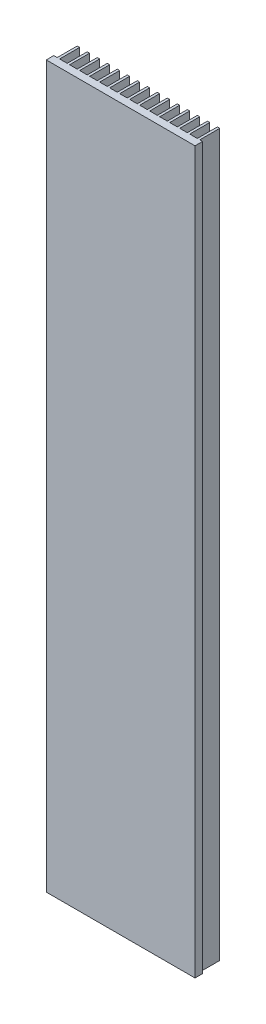
SolidWorks part; units mm, degrees
material "6063-T5"
ref_plane "X-Y Datum" through (0, 0, 0) normal (0, 0, 1) x (1, 0, 0)
ref_plane "X-Z Datum" through (0, 0, 0) normal (0, 1, 0) x (1, 0, 0)
ref_plane "Y-Z Datum" through (0, 0, 0) normal (1, 0, 0) x (0, 0, -1)
sketch "Sketch1" plane through (0, 0, 0) normal (0, 1, 0) x (1, 0, 0)
  line L0 (0, 9.525) -> (4.0132, 9.525) construction
  line L1 (0, 0) -> (136.525, 0)
  line L2 (0, 0) -> (0, 9.525)
  line L3 (0, 9.525) -> (4.0132, 9.525)
  line L4 (136.525, 0) -> (136.525, 9.525)
  line L5 (4.7752, 9.525) -> (4.7752, 34.925) construction
  line L6 (4.0132, 34.925) -> (4.0132, 9.525)
  line L7 (5.5372, 34.925) -> (5.5372, 9.525)
  line L8 (11.8872, 34.925) -> (11.8872, 9.525)
  line L9 (10.3632, 34.925) -> (10.3632, 9.525)
  line L10 (18.2372, 34.925) -> (18.2372, 9.525)
  line L11 (16.7132, 34.925) -> (16.7132, 9.525)
  line L12 (24.5872, 34.925) -> (24.5872, 9.525)
  line L13 (23.0632, 34.925) -> (23.0632, 9.525)
  line L14 (30.9372, 34.925) -> (30.9372, 9.525)
  line L15 (29.4132, 34.925) -> (29.4132, 9.525)
  line L16 (37.2872, 34.925) -> (37.2872, 9.525)
  line L17 (35.7632, 34.925) -> (35.7632, 9.525)
  line L18 (43.6372, 34.925) -> (43.6372, 9.525)
  line L19 (42.1132, 34.925) -> (42.1132, 9.525)
  line L20 (49.9872, 34.925) -> (49.9872, 9.525)
  line L21 (48.4632, 34.925) -> (48.4632, 9.525)
  line L22 (56.3372, 34.925) -> (56.3372, 9.525)
  line L23 (54.8132, 34.925) -> (54.8132, 9.525)
  line L24 (62.6872, 34.925) -> (62.6872, 9.525)
  line L25 (61.1632, 34.925) -> (61.1632, 9.525)
  line L26 (69.0372, 34.925) -> (69.0372, 9.525)
  line L27 (67.5132, 34.925) -> (67.5132, 9.525)
  line L28 (75.3872, 34.925) -> (75.3872, 9.525)
  line L29 (73.8632, 34.925) -> (73.8632, 9.525)
  line L30 (81.7372, 34.925) -> (81.7372, 9.525)
  line L31 (80.2132, 34.925) -> (80.2132, 9.525)
  line L32 (88.0872, 34.925) -> (88.0872, 9.525)
  line L33 (86.5632, 34.925) -> (86.5632, 9.525)
  line L34 (94.4372, 34.925) -> (94.4372, 9.525)
  line L35 (92.9132, 34.925) -> (92.9132, 9.525)
  line L36 (100.7872, 34.925) -> (100.7872, 9.525)
  line L37 (99.2632, 34.925) -> (99.2632, 9.525)
  line L38 (107.1372, 34.925) -> (107.1372, 9.525)
  line L39 (105.6132, 34.925) -> (105.6132, 9.525)
  line L40 (113.4872, 34.925) -> (113.4872, 9.525)
  line L41 (111.9632, 34.925) -> (111.9632, 9.525)
  line L42 (119.8372, 34.925) -> (119.8372, 9.525)
  line L43 (118.3132, 34.925) -> (118.3132, 9.525)
  line L44 (126.1872, 34.925) -> (126.1872, 9.525)
  line L45 (124.6632, 34.925) -> (124.6632, 9.525)
  line L46 (132.5372, 34.925) -> (132.5372, 9.525)
  line L47 (131.0132, 34.925) -> (131.0132, 9.525)
  line L48 (5.5372, 9.525) -> (10.3632, 9.525)
  line L49 (11.8872, 9.525) -> (16.7132, 9.525)
  line L50 (24.5872, 9.525) -> (29.4132, 9.525)
  line L51 (30.9372, 9.525) -> (35.7632, 9.525)
  line L52 (18.2372, 9.525) -> (23.0632, 9.525)
  line L53 (37.2872, 9.525) -> (42.1132, 9.525)
  line L54 (43.6372, 9.525) -> (48.4632, 9.525)
  line L55 (49.9872, 9.525) -> (54.8132, 9.525)
  line L56 (56.3372, 9.525) -> (61.1632, 9.525)
  line L57 (62.6872, 9.525) -> (67.5132, 9.525)
  line L58 (69.0372, 9.525) -> (73.8632, 9.525)
  line L59 (75.3872, 9.525) -> (80.2132, 9.525)
  line L60 (81.7372, 9.525) -> (86.5632, 9.525)
  line L61 (88.0872, 9.525) -> (92.9132, 9.525)
  line L62 (94.4372, 9.525) -> (99.2632, 9.525)
  line L63 (100.7872, 9.525) -> (105.6132, 9.525)
  line L64 (107.1372, 9.525) -> (111.9632, 9.525)
  line L65 (113.4872, 9.525) -> (118.3132, 9.525)
  line L66 (119.8372, 9.525) -> (124.6632, 9.525)
  line L67 (126.1872, 9.525) -> (131.0132, 9.525)
  line L68 (132.5372, 9.525) -> (136.525, 9.525)
  arc A0 (5.5372, 34.925) -> (4.0132, 34.925) centre (4.7752, 34.925) ccw
  arc A1 (11.8872, 34.925) -> (10.3632, 34.925) centre (11.1252, 34.925) ccw
  arc A2 (18.2372, 34.925) -> (16.7132, 34.925) centre (17.4752, 34.925) ccw
  arc A3 (24.5872, 34.925) -> (23.0632, 34.925) centre (23.8252, 34.925) ccw
  arc A4 (30.9372, 34.925) -> (29.4132, 34.925) centre (30.1752, 34.925) ccw
  arc A5 (37.2872, 34.925) -> (35.7632, 34.925) centre (36.5252, 34.925) ccw
  arc A6 (43.6372, 34.925) -> (42.1132, 34.925) centre (42.8752, 34.925) ccw
  arc A7 (49.9872, 34.925) -> (48.4632, 34.925) centre (49.2252, 34.925) ccw
  arc A8 (56.3372, 34.925) -> (54.8132, 34.925) centre (55.5752, 34.925) ccw
  arc A9 (62.6872, 34.925) -> (61.1632, 34.925) centre (61.9252, 34.925) ccw
  arc A10 (69.0372, 34.925) -> (67.5132, 34.925) centre (68.2752, 34.925) ccw
  arc A11 (75.3872, 34.925) -> (73.8632, 34.925) centre (74.6252, 34.925) ccw
  arc A12 (81.7372, 34.925) -> (80.2132, 34.925) centre (80.9752, 34.925) ccw
  arc A13 (88.0872, 34.925) -> (86.5632, 34.925) centre (87.3252, 34.925) ccw
  arc A14 (94.4372, 34.925) -> (92.9132, 34.925) centre (93.6752, 34.925) ccw
  arc A15 (100.7872, 34.925) -> (99.2632, 34.925) centre (100.0252, 34.925) ccw
  arc A16 (107.1372, 34.925) -> (105.6132, 34.925) centre (106.3752, 34.925) ccw
  arc A17 (113.4872, 34.925) -> (111.9632, 34.925) centre (112.7252, 34.925) ccw
  arc A18 (119.8372, 34.925) -> (118.3132, 34.925) centre (119.0752, 34.925) ccw
  arc A19 (126.1872, 34.925) -> (124.6632, 34.925) centre (125.4252, 34.925) ccw
  arc A20 (132.5372, 34.925) -> (131.0132, 34.925) centre (131.7752, 34.925) ccw
  dimension "D1" = 21
extrude "Boss-Extrude1" add sketch "Sketch1" along normal blind 457.2
sketch "Sketch2" plane through (0, 457.2, 0) normal (0, 1, 0) x (1, 0, 0)
  line L0 (136.525, 0) -> (136.525, 9.525) construction
  line L1 (0, 0) -> (136.525, 0)
  line L2 (0, 0) -> (0, 4.7625)
  line L3 (0, 4.7625) -> (136.525, 4.7625)
  line L4 (136.525, 0) -> (136.525, 4.7625)
extrude "Cut-Extrude1" cut sketch "Sketch2" against normal through all
sketch "Sketch3" plane through (0, 0, 0) normal (0, -1, 0) x (1, 0, 0)
  line L1 (3.1502, -35.687) -> (135.4162, -35.687)
  line L2 (3.1502, -35.687) -> (3.1502, -22.225)
  line L3 (3.1502, -22.225) -> (135.4162, -22.225)
  line L4 (135.4162, -35.687) -> (135.4162, -22.225)
extrude "Cut-Extrude2" cut sketch "Sketch3" against normal through all
sketch "Sketch7" plane through (0, 0, 0) normal (0, -1, 0) x (1, 0, 0)
  line L0 (0, -4.7625) -> (101.6, -4.7625) construction
  line L1 (136.525, -4.7625) -> (0, -4.7625) construction
  line L3 (136.525, -4.7625) -> (101.6, -4.7625)
  line L4 (136.525, -4.7625) -> (136.525, -25.7283)
  line L5 (136.525, -25.7283) -> (101.6, -25.7283)
  line L6 (101.6, -4.7625) -> (101.6, -25.7283)
sketch "Sketch9" plane through (0, 0, -4.7625) normal (0, 0, 1) x (1, 0, 0)
  line L1 (20.8921, -2.4045) -> (115.2525, -2.4045)
  line L2 (20.8921, -2.4045) -> (20.8921, 479.2699)
  line L3 (20.8921, 479.2699) -> (115.2525, 479.2699)
  line L4 (115.2525, -2.4045) -> (115.2525, 479.2699)
  line L5 (20.8921, -2.4045) -> (115.2525, 479.2699) construction
  line L6 (20.8921, 479.2699) -> (115.2525, -2.4045) construction
  point P0 (68.0723, 238.4327)
extrude "Cut-Extrude3" cut sketch "Sketch9" against normal through all flip side to cut
